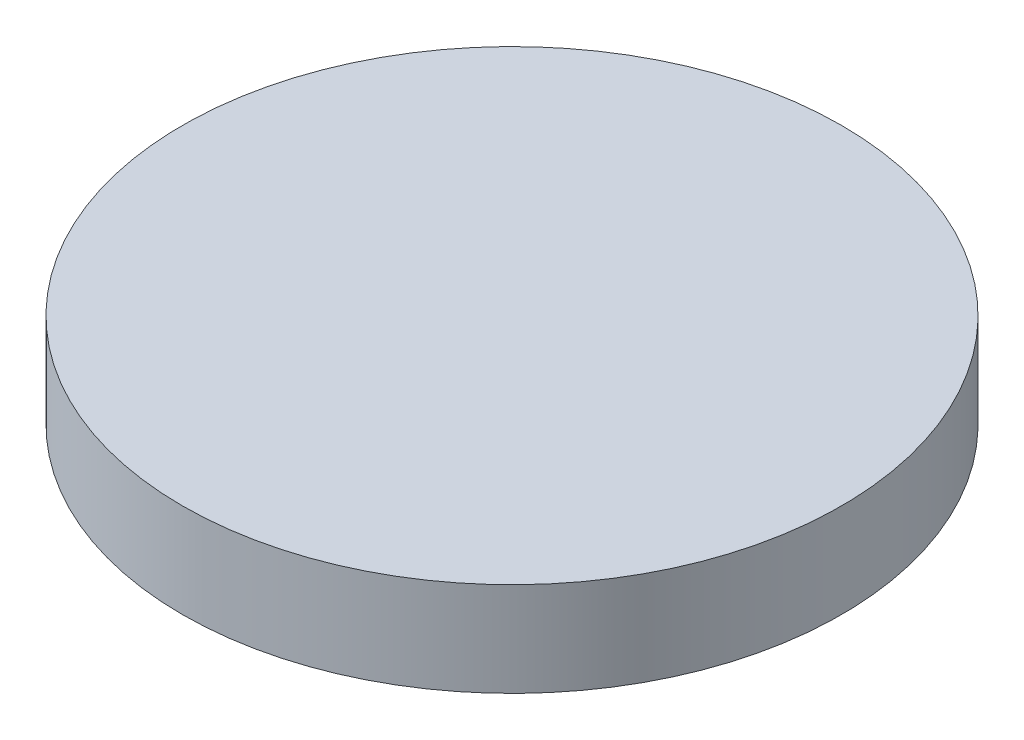
SolidWorks part; units mm, degrees
material "Хромистая нержавеющая сталь"
ref_plane "Front" through (0, 0, 0) normal (0, 0, 1) x (1, 0, 0)
ref_plane "Top" through (0, 0, 0) normal (0, 1, 0) x (1, 0, 0)
ref_plane "Right" through (0, 0, 0) normal (1, 0, 0) x (0, 0, -1)
sketch "Эскиз1" plane through (0, 0, 0) normal (0, 1, 0) x (1, 0, 0)
  circle A0 centre (0, 0) radius 3.5
  dimension "D1" = 7
extrude "База" add sketch "Эскиз1" along normal blind 1
